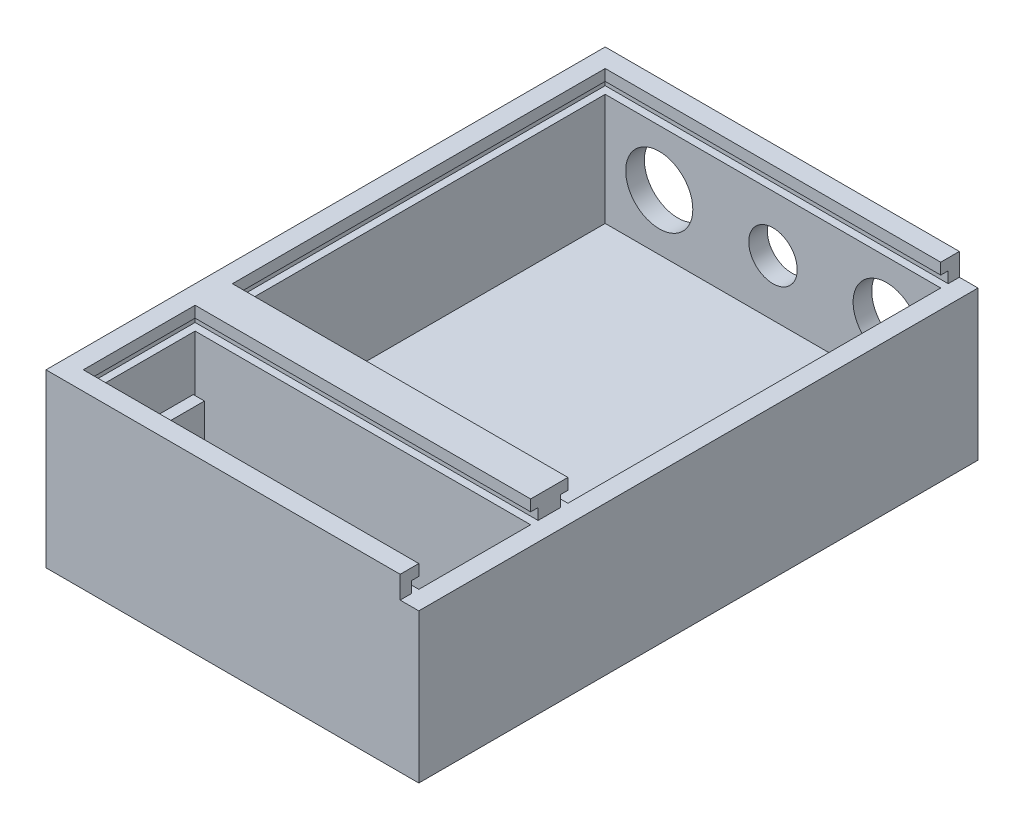
SolidWorks part; units mm, degrees
ref_plane "Front Plane" through (0, 0, 0) normal (0, 0, 1) x (1, 0, 0)
ref_plane "Top Plane" through (0, 0, 0) normal (0, 1, 0) x (1, 0, 0)
ref_plane "Right Plane" through (0, 0, 0) normal (1, 0, 0) x (0, 0, -1)
sketch "Sketch1" plane through (0, 0, 0) normal (0, 0, 1) x (1, 0, 0)
  line L0 (6.2525, 13.33) -> (6.2525, -26.67) construction
  line L1 (-43.7475, 13.33) -> (56.2525, 13.33)
  line L2 (-43.7475, 13.33) -> (-43.7475, -26.67)
  line L3 (-43.7475, -26.67) -> (56.2525, -26.67)
  line L4 (56.2525, 13.33) -> (56.2525, -26.67)
  line L5 (-43.7475, -6.67) -> (56.2525, -6.67) construction
  line L6 (6.2525, -6.67) -> (36.7525, -6.67)
  line L7 (6.2525, -6.67) -> (-24.2475, -6.67)
  circle A0 centre (6.2525, -6.67) radius 6.5
  circle A1 centre (36.7525, -6.67) radius 9
  circle A2 centre (-24.2475, -6.67) radius 9
  dimension "D3" = 13
  dimension "D5" = 18
  dimension "D7" = 18
  dimension "D1" = 100
  dimension "D2" = 40
  dimension "D4" = 30.5
  dimension "D6" = 30.5
extrude "Boss-Extrude1" add sketch "Sketch1" along normal blind 150 contours L2 L1 L4 L3
sketch "Sketch2" plane through (0, 13.33, 0) normal (0, 1, 0) x (1, 0, 0)
  line L0 (6.2525, 0) -> (6.2525, -150) construction
  line L2 (56.2525, -75) -> (-43.7475, -75) construction
  line L3 (56.2525, -150) -> (56.2525, 0) construction
  line L4 (-43.7475, -150) -> (-43.7475, 0) construction
  line L5 (-43.7475, 0) -> (56.2525, 0) construction
  line L10 (-43.7475, -150) -> (56.2525, -150) construction
  line L11 (-38.7475, -145) -> (51.2525, -145)
  line L12 (-38.7475, -145) -> (-38.7475, -5)
  line L13 (-38.7475, -5) -> (51.2525, -5)
  line L14 (51.2525, -145) -> (51.2525, -5)
  line L15 (-38.7475, -145) -> (51.2525, -5) construction
  line L16 (-38.7475, -5) -> (51.2525, -145) construction
  point P4 (6.2525, -75)
  dimension "D1" = 90
  dimension "D2" = 90
  dimension "D3" = 140
extrude "Cut-Extrude1" cut sketch "Sketch2" against normal blind 30 contours L12 L11 L14 L13
sketch "Sketch4" plane through (0, 0, 0) normal (0, 1, 0) x (1, 0, 0)
  line L2 (-38.7475, -145) -> (-38.7475, -115)
  line L7 (-38.7475, -145) -> (-38.7475, -5) construction
  dimension "D1" = 30
ref_plane "Plane1" through (0, 13.33, 0) normal (0, 1, 0) x (1, 0, 0)
sketch "Sketch5" plane through (0, 13.33, 0) normal (0, 1, 0) x (1, 0, 0)
  line L0 (51.2525, -145) -> (51.2525, -5) construction
  line L1 (-38.7475, -115) -> (51.2525, -115)
  line L2 (-38.7475, -115) -> (-38.7475, -105)
  line L3 (-38.7475, -105) -> (51.2525, -105)
  line L4 (51.2525, -115) -> (51.2525, -105)
  dimension "D1" = 10
extrude "Boss-Extrude3" add sketch "Sketch5" against normal up to surface (30 mm away) up to face at (6.2525, -16.67, 75)
sketch "Sketch8" plane through (0, 13.33, 0) normal (0, 1, 0) x (1, 0, 0)
  line L6 (-43.7475, -150) -> (56.2525, -150) construction
  line L8 (-43.7475, -113) -> (-43.7475, -150)
  line L9 (-43.7475, -150) -> (-40.7475, -150)
  line L10 (-40.7475, -113) -> (-40.7475, -147)
  line L12 (-40.7475, -150) -> (51.2525, -150)
  line L14 (-40.7475, -147) -> (51.2525, -147)
  line L15 (51.2525, -150) -> (51.2525, -147)
  line L16 (-40.7475, -113) -> (51.2525, -113)
  line L17 (-43.7475, -113) -> (-43.7475, -110)
  line L18 (-43.7475, -110) -> (51.2525, -110)
  line L19 (51.2525, -113) -> (51.2525, -110)
  dimension "D1" = 95
  dimension "D2" = 3
  dimension "D3" = 2
  dimension "D4" = 3
  dimension "D5" = 92
  dimension "D6" = 3
  dimension "D7" = 34
extrude "Boss-Extrude6" add sketch "Sketch8" along normal blind 6
sketch "Sketch10" plane through (0, 19.33, 0) normal (0, 1, 0) x (1, 0, 0)
  line L0 (51.2525, -113) -> (51.2525, -115)
  line L1 (51.2525, -115) -> (-38.7475, -115)
  line L2 (-38.7475, -115) -> (-38.7475, -145)
  line L3 (-38.7475, -145) -> (51.2525, -145)
  line L4 (51.2525, -145) -> (51.2525, -147)
  line L5 (51.2525, -147) -> (-40.7475, -147) construction
  line L6 (51.2525, -147) -> (-40.7475, -147) construction
  line L7 (51.2525, -147) -> (-40.7475, -147)
  line L8 (-40.7475, -147) -> (-40.7475, -113)
  line L9 (-40.7475, -113) -> (51.2525, -113)
extrude "Boss-Extrude7" add sketch "Sketch10" against normal blind 3
ref_plane "Plane3" through (0, 19.33, 0) normal (0, 1, 0) x (1, 0, 0)
sketch "Sketch11" plane through (0, 19.33, 0) normal (0, 1, 0) x (1, 0, 0)
  line L0 (51.2525, -110) -> (51.2525, -105)
  line L1 (51.2525, -105) -> (-38.7475, -105)
  line L2 (-38.7475, -105) -> (-38.7475, -5)
  line L3 (-38.7475, -5) -> (51.2525, -5)
  line L4 (51.2525, -5) -> (51.2525, 0)
  line L5 (-43.7475, 0) -> (56.2525, 0) construction
  line L6 (51.2525, 0) -> (-43.7475, 0)
  line L7 (-43.7475, 0) -> (-43.7475, -110)
  line L8 (-43.7475, -110) -> (51.2525, -110)
  line L10 (51.2525, -110) -> (51.2525, -107)
  line L11 (-43.7475, -110) -> (-40.7475, -110)
  line L12 (-43.7475, 0) -> (-43.7475, -3)
  line L13 (51.2525, -107) -> (-40.7475, -107)
  line L14 (-40.7475, -107) -> (-40.7475, -3)
  line L15 (-40.7475, -3) -> (51.2525, -3)
  line L16 (51.2525, -3) -> (51.2525, 0)
  line L17 (-43.7475, 0) -> (-43.7475, -110)
  dimension "D1" = 3
  dimension "D2" = 3
  dimension "D3" = 3
extrude "Boss-Extrude8" add sketch "Sketch11" against normal up to surface (6 mm away) contours L8 L0 L1 L2 L3 L4 L6 L7 up to face at (14.8525, 13.33, 104)
sketch "Sketch13" plane through (0, 13.33, 0) normal (0, 1, 0) x (1, 0, 0)
  line L1 (51.2525, 0) -> (51.2525, -5) construction
  line L2 (51.2525, -3) -> (-40.7475, -3)
  line L3 (51.2525, -105) -> (51.2525, -107)
  line L5 (51.2525, -115) -> (51.2525, -105) construction
  line L6 (51.2525, -107) -> (-40.7475, -107)
  line L7 (-40.7475, -107) -> (-40.7475, -3)
  line L8 (51.2525, -3) -> (51.2525, -5)
  line L9 (51.2525, -105) -> (-38.7475, -105)
  line L11 (-38.7475, -105) -> (-38.7475, -5)
  line L12 (-38.7475, -5) -> (51.2525, -5)
  dimension "D1" = 92
  dimension "D2" = 2
  dimension "D3" = 2
extrude "Cut-Extrude7" cut sketch "Sketch13" along normal blind 3
ref_plane "Plane10" through (0, -16.67, 0) normal (0, 1, 0) x (1, 0, 0)
sketch "Sketch14" plane through (0, -16.67, 0) normal (0, 1, 0) x (1, 0, 0)
  line L0 (6.2525, -115) -> (6.2525, -145) construction
  line L1 (51.2525, -115) -> (-38.7475, -115) construction
  line L2 (-38.7475, -145) -> (51.2525, -145) construction
  line L3 (-38.7475, -130) -> (51.2525, -130) construction
  line L4 (-38.7475, -145) -> (-38.7475, -115) construction
  line L5 (51.2525, -145) -> (51.2525, -115) construction
  line L7 (-31.2475, -140) -> (43.7525, -140)
  line L8 (-31.2475, -140) -> (-31.2475, -120)
  line L9 (-31.2475, -120) -> (43.7525, -120)
  line L10 (43.7525, -140) -> (43.7525, -120)
  line L11 (-31.2475, -140) -> (43.7525, -120) construction
  line L12 (-31.2475, -120) -> (43.7525, -140) construction
  line L13 (-31.2475, -120) -> (-34.2475, -120)
  line L14 (-31.2475, -120) -> (-31.2475, -140)
  line L15 (-31.2475, -140) -> (-34.2475, -140)
  line L16 (-34.2475, -120) -> (-34.2475, -140)
  point P12 (6.2525, -130)
  dimension "D1" = 75
  dimension "D2" = 20
  dimension "D3" = 3
extrude "Boss-Extrude9" add sketch "Sketch14" along normal blind 20 contours L13 L16 L15 L8
sketch "Sketch15" plane through (0, -16.67, 0) normal (0, 1, 0) x (1, 0, 0)
  line L3 (46.7525, -140) -> (43.7525, -140)
  line L4 (46.7525, -140) -> (46.7525, -120)
  line L5 (46.7525, -120) -> (43.7525, -120)
  line L6 (43.7525, -140) -> (43.7525, -120)
  dimension "D2" = 3
extrude "Boss-Extrude10" add sketch "Sketch15" along normal blind 20
sketch "Sketch16" plane through (0, -16.67, 0) normal (0, 1, 0) x (1, 0, 0)
  line L6 (-31.2475, -140) -> (-31.2475, -142)
  line L9 (-11.2475, -120) -> (23.7525, -120)
  line L13 (23.7525, -120) -> (23.7525, -122)
  line L14 (23.7525, -122) -> (-11.2475, -122)
  line L15 (-11.2475, -122) -> (-11.2475, -120)
  dimension "D1" = 2
  dimension "D2" = 35
extrude "Boss-Extrude11" add sketch "Sketch16" along normal blind 10 contours L15 L9 L13 L14
sketch "Sketch17" plane through (0, -16.67, 0) normal (0, 1, 0) x (1, 0, 0)
  line L1 (23.7525, -140) -> (23.7525, -137.9983)
  line L2 (23.7525, -137.9983) -> (-11.2475, -137.9983)
  line L3 (-11.2475, -137.9983) -> (-11.2475, -140)
  line L4 (-11.2475, -140) -> (23.7525, -140)
  dimension "D1" = 2.0017
extrude "Boss-Extrude12" add sketch "Sketch17" along normal blind 10
sketch "Sketch18" plane through (0, 0, 0) normal (0, 0, 1) x (1, 0, 0)
  line L0 (56.2525, 13.33) -> (56.2525, -26.67) construction
  line L1 (-43.7475, 19.33) -> (-43.7475, -26.67) construction
  line L2 (51.2525, 13.33) -> (56.2525, 13.33) construction
  circle A0 centre (6.2525, -1.67) radius 6.5
  circle A2 centre (36.7525, -1.67) radius 9
  circle A3 centre (-24.2475, -1.67) radius 9
  point P8 (56.2525, -9.1606)
  point P11 (0, 0)
  dimension "D1" = 13
  dimension "D2" = 30.5
  dimension "D3" = 50
  dimension "D4" = 18
  dimension "D7" = 18
  dimension "D5" = 50
  dimension "D6" = 30.5
  dimension "D8" = 15
extrude "Cut-Extrude9" cut sketch "Sketch18" along normal blind 10
